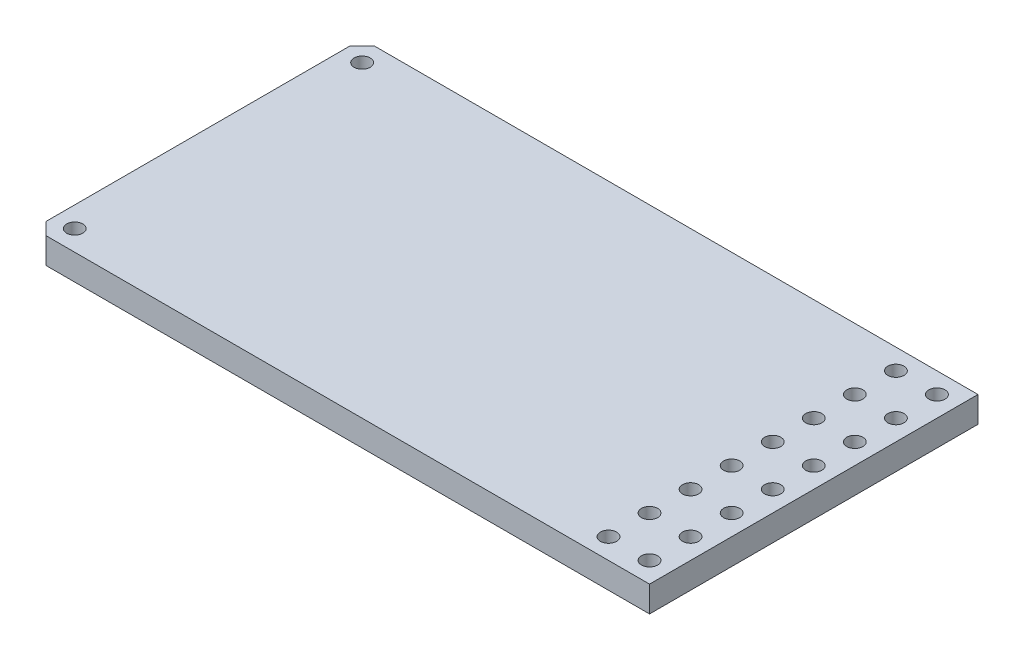
SolidWorks part; units mm, degrees
ref_plane "Front Plane" through (0, 0, 0) normal (0, 0, 1) x (1, 0, 0)
ref_plane "Top Plane" through (0, 0, 0) normal (0, 1, 0) x (1, 0, 0)
ref_plane "Right Plane" through (0, 0, 0) normal (1, 0, 0) x (0, 0, -1)
sketch "Sketch1" plane through (0, 0, 0) normal (0, 1, 0) x (1, 0, 0)
  line L0 (-55, 0) -> (55, 0) construction
  line L1 (-19.05, -10.16) -> (19.05, -10.16)
  line L2 (-19.05, -10.16) -> (-19.05, 10.16)
  line L3 (-19.05, 10.16) -> (19.05, 10.16)
  line L4 (19.05, -10.16) -> (19.05, 10.16)
  line L5 (-19.05, -10.16) -> (19.05, 10.16) construction
  line L6 (-19.05, 10.16) -> (19.05, -10.16) construction
  line L7 (-18.288, 10.16) -> (-19.05, 9.398)
  line L8 (-18.288, -10.16) -> (-19.05, -9.398)
  circle A0 centre (-17.78, 8.89) radius 0.5
  circle A1 centre (-17.78, -8.89) radius 0.5
  circle A2 centre (17.78, 8.89) radius 0.5
  circle A3 centre (15.24, 8.89) radius 0.5
  circle A4 centre (15.24, 6.35) radius 0.5
  circle A5 centre (17.78, 6.35) radius 0.5
  circle A6 centre (15.24, 3.81) radius 0.5
  circle A7 centre (17.78, 3.81) radius 0.5
  circle A8 centre (15.24, 1.27) radius 0.5
  circle A9 centre (17.78, 1.27) radius 0.5
  circle A10 centre (15.24, -1.27) radius 0.5
  circle A11 centre (17.78, -1.27) radius 0.5
  circle A12 centre (15.24, -3.81) radius 0.5
  circle A13 centre (17.78, -3.81) radius 0.5
  circle A14 centre (15.24, -6.35) radius 0.5
  circle A15 centre (17.78, -6.35) radius 0.5
  circle A16 centre (15.24, -8.89) radius 0.5
  circle A17 centre (17.78, -8.89) radius 0.5
  point P21 (0, 0)
  point P48 (15.3283, 8.89)
  dimension "D3" = 1
  dimension "D1" = 38.1
  dimension "D2" = 20.32
  dimension "D4" = 17.78
  dimension "D5" = 1.27
  dimension "D6" = 0.762
  dimension "D7" = 0.762
  dimension "D9" = 1.27
  dimension "D10" = 2.54
  dimension "D11" = 2.54
  dimension "D8" = 8
extrude "Boss-Extrude1" add sketch "Sketch1" along normal mid plane 1.6 contours L8 L1 L4 L3 L7 L2 A0 A1
